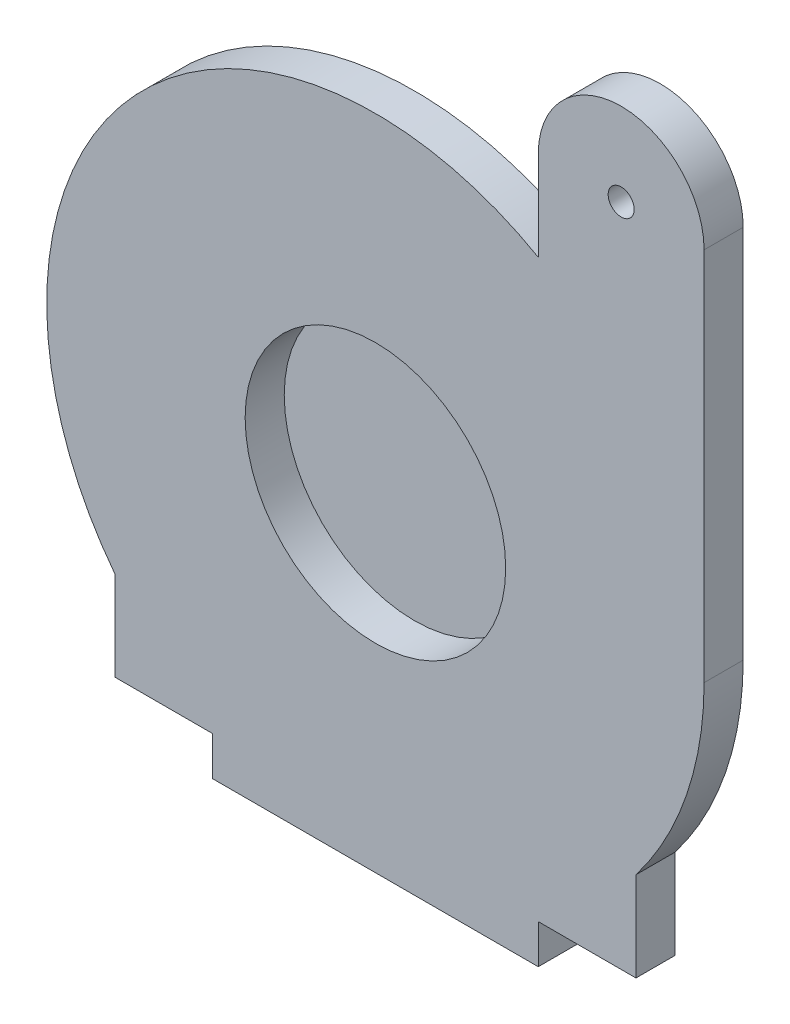
SolidWorks part; units mm, degrees
ref_plane "Front Plane" through (0, 0, 0) normal (0, 0, 1) x (1, 0, 0)
ref_plane "Top Plane" through (0, 0, 0) normal (0, 1, 0) x (1, 0, 0)
ref_plane "Right Plane" through (0, 0, 0) normal (1, 0, 0) x (0, 0, -1)
sketch "Sketch1" plane through (0, 0, 0) normal (0, 0, 1) x (1, 0, 0)
  line L0 (0, 0) -> (7.5, 0)
  line L1 (7.5, 0) -> (7.5, -3)
  line L2 (7.5, -3) -> (32.5, -3)
  line L3 (32.5, -3) -> (32.5, 0)
  line L4 (32.5, 0) -> (40, 0)
  line L8 (7.5, 0) -> (32.5, 0) construction
  line L9 (0, 0) -> (0, 6.8671)
  line L10 (40, 0) -> (40, 6.8671)
  line L11 (45.2315, 22.2499) -> (45.2315, 51.0239)
  line L12 (32.5, 44.1674) -> (32.5, 51.0239)
  circle A2 centre (20, 22.2499) radius 17.2656
  arc A7 (40, 6.8671) -> (45.2315, 22.2499) centre (20, 22.2499) ccw
  arc A8 (32.5, 51.0239) -> (45.2315, 51.0239) centre (38.8658, 51.0239) cw
  circle A9 centre (38.8658, 51.0239) radius 1
  arc A10 (32.5, 44.1674) -> (0, 6.8671) centre (20, 22.2499) ccw
  circle A11 centre (20, 22.2499) radius 10
  point P18 (45.2315, 22.2499)
  point P23 (32.5, 44.1674)
  dimension "D5" = 20
  dimension "D3" = 2
  dimension "D1" = 25
  dimension "D2" = 3
  dimension "D4" = 7.5
extrude "Boss-Extrude5" add sketch "Sketch1" along normal blind 3 contours A2 A11 | L0 L8 L4 L10 A7 L11 A8 L12 A10 L9 A2 A9 | L8 L1 L2 L3
sketch "Sketch2" plane through (0, 0, 0) normal (0, 0, -1) x (-1, 0, 0)
  circle A0 centre (-20, 22.2499) radius 17.5
  dimension "D1" = 35
extrude "Boss-Extrude6" add sketch "Sketch2" along normal blind 3.5
